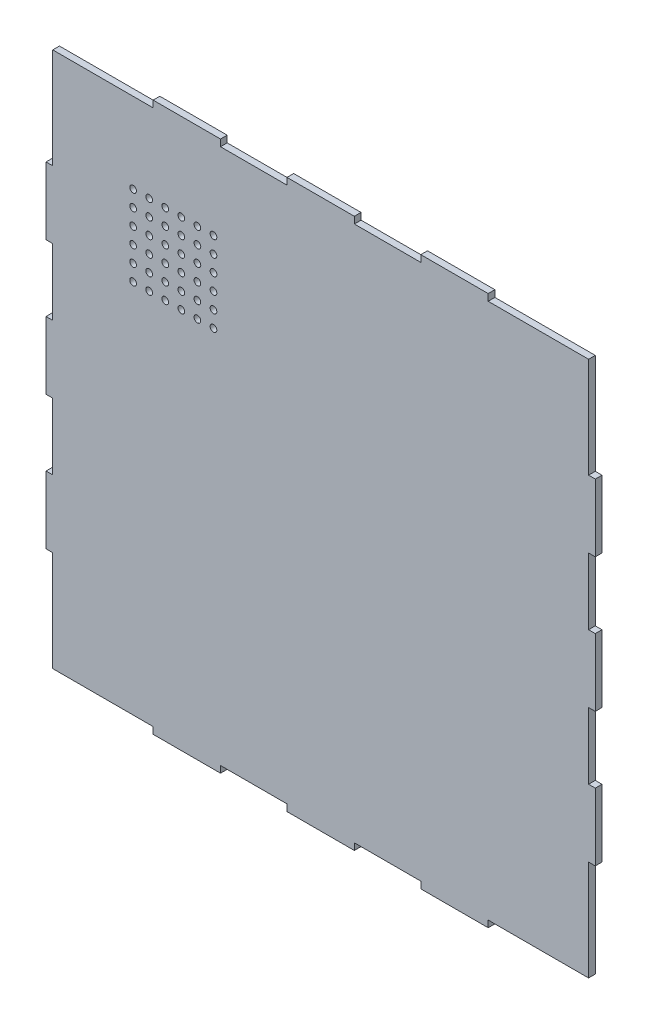
SolidWorks part; units mm, degrees
ref_plane "Ebene vorne" through (0, 0, 0) normal (0, 0, 1) x (1, 0, 0)
ref_plane "Ebene oben" through (0, 0, 0) normal (0, 1, 0) x (1, 0, 0)
ref_plane "Ebene rechts" through (0, 0, 0) normal (1, 0, 0) x (0, 0, -1)
sketch "Skizze1" plane through (0, 0, 0) normal (0, 0, 1) x (1, 0, 0)
  line L1 (0, 0) -> (410, 0)
  line L2 (0, 0) -> (0, 410)
  line L3 (0, 410) -> (410, 410)
  line L4 (410, 0) -> (410, 410)
  dimension "D1" = 410
  dimension "D2" = 410
extrude "Aufsatz-Linear austragen1" add sketch "Skizze1" along normal blind 5 contours L2 L3 L4 L1
sketch "Skizze2" plane through (0, 0, 5) normal (0, 0, 1) x (1, 0, 0)
  line L0 (0, 410) -> (410, 410) construction
  line L1 (-92.7967, 379.65) -> (5, 379.65)
  line L2 (-92.7967, 379.65) -> (-92.7967, 330.05)
  line L3 (-92.7967, 330.05) -> (5, 330.05)
  line L4 (5, 379.65) -> (5, 330.05)
  dimension "D1" = 49.6
  dimension "D2" = 5
  dimension "D3" = 79.95
extrude "Schnitt-Linear austragen1" cut sketch "Skizze2" against normal blind 5
pattern_linear "Lineares Muster1" count 4 spacing 99.9 along (0, -1, 0) of "Schnitt-Linear austragen1"
ref_plane "Ebene1" through (205, 0, 0) normal (1, 0, 0) x (0, 0, -1)
mirror "Spiegeln1" about plane through (205, 0, 0) normal (1, 0, 0) of "Schnitt-Linear austragen1", "Lineares Muster1"
sketch "Skizze3" plane through (0, 0, 5) normal (0, 0, 1) x (1, 0, 0)
  line L0 (0, 410) -> (410, 410) construction
  line L1 (30.35, 446.7791) -> (79.95, 446.7791)
  line L2 (30.35, 446.7791) -> (30.35, 405)
  line L3 (30.35, 405) -> (79.95, 405)
  line L4 (79.95, 446.7791) -> (79.95, 405)
  dimension "D1" = 49.6
  dimension "D2" = 5
  dimension "D3" = 79.95
extrude "Schnitt-Linear austragen2" cut sketch "Skizze3" against normal blind 5
pattern_linear "Lineares Muster2" count 4 spacing 99.9 along (1, 0, 0) of "Schnitt-Linear austragen2"
ref_plane "Ebene2" through (0, 205, 0) normal (0, 1, 0) x (1, 0, 0)
mirror "Spiegeln2" about plane through (0, 205, 0) normal (0, 1, 0) of "Schnitt-Linear austragen2", "Lineares Muster2"
sketch "Skizze4" plane through (0, 0, 5) normal (0, 0, 1) x (1, 0, 0)
  line L0 (5, 379.65) -> (5, 405)
  line L1 (30.35, 405) -> (5, 405)
  line L7 (5, 379.65) -> (-47.8629, 379.65)
  line L10 (-47.8629, 379.65) -> (-47.8629, 405)
  line L12 (-47.8629, 405) -> (-47.8629, 431.5498)
  line L13 (-47.8629, 431.5498) -> (5, 431.5498)
  line L17 (5, 431.5498) -> (30.35, 431.5498)
  line L18 (30.35, 405) -> (30.35, 431.5498)
extrude "Schnitt-Linear austragen3" cut sketch "Skizze4" against normal blind 5
mirror "Spiegeln3" about plane through (205, 0, 0) normal (1, 0, 0) of "Schnitt-Linear austragen3"
mirror "Spiegeln4" about plane through (0, 205, 0) normal (0, 1, 0) of "Schnitt-Linear austragen3", "Spiegeln3"
sketch "Skizze5" plane through (0, 0, 5) normal (0, 0, 1) x (1, 0, 0)
  line L1 (5, 330.05) -> (5, 405) construction
  line L2 (5, 405) -> (79.95, 405) construction
  circle A0 centre (125, 285) radius 2.5
  dimension "D1" = 5
  dimension "D2" = 120
  dimension "D3" = 120
extrude "Schnitt-Linear austragen4" cut sketch "Skizze5" against normal blind 10 contours A0
pattern_linear "Lineares Muster3" count 6 spacing 12 along (0, 1, 0) count 6 spacing 12 along (-1, 0, 0) of "Schnitt-Linear austragen4"
